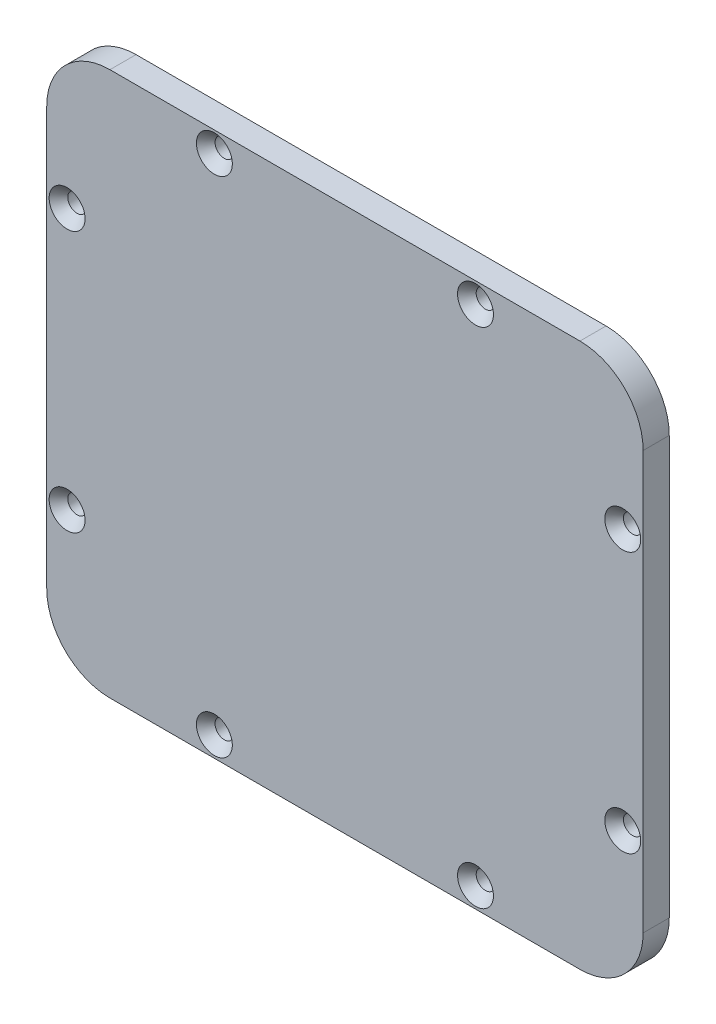
SolidWorks part; units mm, degrees
ref_plane "Front Plane" through (0, 0, 0) normal (0, 0, 1) x (1, 0, 0)
ref_plane "Top Plane" through (0, 0, 0) normal (0, 1, 0) x (1, 0, 0)
ref_plane "Right Plane" through (0, 0, 0) normal (1, 0, 0) x (0, 0, -1)
sketch "Sketch1" plane through (0, 0, 0) normal (0, 0, 1) x (1, 0, 0)
  line L8 (-36.2585, 25.4) -> (-36.2585, -25.4)
  line L9 (28.575, 33.0835) -> (-28.575, 33.0835)
  line L10 (36.2585, -25.4) -> (36.2585, 25.4)
  line L11 (-28.575, -33.0835) -> (28.575, -33.0835)
  line L12 (-36.2585, 25.4) -> (-36.2585, -25.4)
  line L13 (28.575, 33.0835) -> (-28.575, 33.0835)
  line L14 (36.2585, -25.4) -> (36.2585, 25.4)
  line L15 (-28.575, -33.0835) -> (28.575, -33.0835)
  arc A8 (-28.575, 33.0835) -> (-36.2585, 25.4) centre (-28.575, 25.4) ccw
  arc A9 (36.2585, 25.4) -> (28.575, 33.0835) centre (28.575, 25.4) ccw
  arc A10 (28.575, -33.0835) -> (36.2585, -25.4) centre (28.575, -25.4) ccw
  arc A11 (-36.2585, -25.4) -> (-28.575, -33.0835) centre (-28.575, -25.4) ccw
  arc A12 (-28.575, 33.0835) -> (-36.2585, 25.4) centre (-28.575, 25.4) ccw
  arc A13 (36.2585, 25.4) -> (28.575, 33.0835) centre (28.575, 25.4) ccw
  arc A14 (28.575, -33.0835) -> (36.2585, -25.4) centre (28.575, -25.4) ccw
  arc A15 (-36.2585, -25.4) -> (-28.575, -33.0835) centre (-28.575, -25.4) ccw
  dimension "D1" = 0.254
extrude "Boss-Extrude1" add sketch "Sketch1" along normal blind 3.175
hole_wizard "CSK for #2 Flat Head Machine Screw1" positions "Sketch2" profile "Sketch3" countersink size "#2" standard "ANSI Inch" end condition through all
sketch "Sketch2" plane through (13.4356, 90.2468, 3.175) normal (0, 0, 1) x (1, 0, 0)
  point P0 (-29.3106, -59.6398)
  point P2 (-47.2176, -74.3718)
  point P4 (-47.2176, -106.1218)
  point P6 (-29.3106, -120.8538)
  point P8 (2.4394, -120.8538)
  point P10 (20.3464, -106.1218)
  point P12 (20.3464, -74.3718)
  point P14 (2.4394, -59.6398)
sketch "Sketch3" plane through (-15.875, 30.607, 3.175) normal (1, 0, 0) x (0, -1, 0)
  line L0 (0, 0) -> (0, 3.175)
  line L1 (0, 3.175) -> (1.1303, 3.175)
  line L2 (1.1303, 3.175) -> (1.1303, 1.2126)
  line L3 (1.1303, 1.2126) -> (2.1844, 0)
  line L4 (2.1844, 0) -> (0, 0)
  line L5 (-1.1303, 1.2126) -> (-2.1844, 0) construction
  line L6 (0, -6.35) -> (0, 107.95) construction
  dimension "Thru Hole Dia." = 2.2606
  dimension "Thru Hole Depth" = 3.175
  dimension "Near C'Sink Dia." = 4.3688
  dimension "Near C'Sink Angle" = 82
